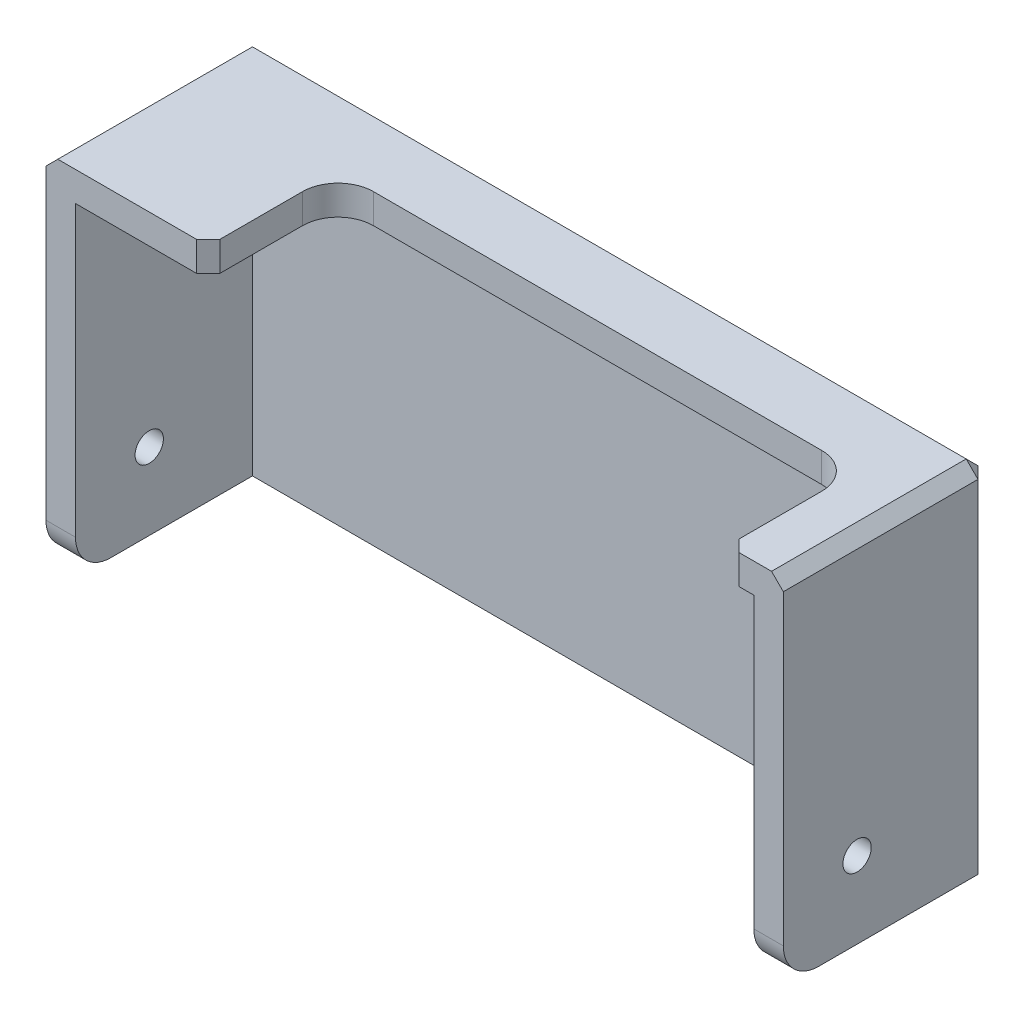
SolidWorks part; units mm, degrees
ref_plane "Front Plane" through (0, 0, 0) normal (0, 0, 1) x (1, 0, 0)
ref_plane "Top Plane" through (0, 0, 0) normal (0, 1, 0) x (1, 0, 0)
ref_plane "Right Plane" through (0, 0, 0) normal (1, 0, 0) x (0, 0, -1)
sketch "Sketch1" plane through (0, 0, 0) normal (0, 0, 1) x (1, 0, 0)
  line L1 (-57.5, -27.5) -> (57.5, -27.5)
  line L2 (-57.5, -27.5) -> (-57.5, 27.5)
  line L3 (-57.5, 27.5) -> (57.5, 27.5)
  line L4 (57.5, -27.5) -> (57.5, 27.5)
  line L5 (-57.5, -27.5) -> (57.5, 27.5) construction
  line L6 (-57.5, 27.5) -> (57.5, -27.5) construction
  point P0 (0, 0)
  dimension "D1" = 55
  dimension "D2" = 115
extrude "Boss-Extrude1" add sketch "Sketch1" along normal blind 30
sketch "Sketch2" plane through (0, 27.5, 0) normal (0, 1, 0) x (1, 0, 0)
  line L0 (57.5, -30) -> (-57.5, -30) construction
  line L1 (-35, -30) -> (53, -30)
  line L2 (-35, -30) -> (-35, -8)
  line L3 (-35, -8) -> (53, -8)
  line L4 (53, -30) -> (53, -8)
  line L6 (57.5, -30) -> (57.5, 0) construction
  line L7 (-57.5, -30) -> (-57.5, 0) construction
  dimension "D1" = 22.5
  dimension "D2" = 4.5
  dimension "D3" = 22
extrude "Cut-Extrude1" cut sketch "Sketch2" against normal through all
sketch "Sketch3" plane through (0, 0, 30) normal (0, 0, 1) x (1, 0, 0)
  line L0 (53, -27.5) -> (57.5, -27.5) construction
  line L1 (57.25, -27.5) -> (-57.25, -27.5)
  line L2 (57.25, -27.5) -> (57.25, 17.5)
  line L3 (57.25, 17.5) -> (-57.25, 17.5)
  line L4 (-57.25, -27.5) -> (-57.25, 17.5)
  line L5 (0, 17.5) -> (0, -27.5) construction
  line L7 (57.5, 27.5) -> (53, 27.5) construction
  dimension "D1" = 114.5
  dimension "D2" = 10
extrude "Cut-Extrude2" [suppressed] cut sketch "Sketch3" against normal blind 30
shell "Shell1" thickness 5
sketch "Sketch6" plane through (-62.5, 0, 0) normal (-1, 0, 0) x (0, 0, 1)
  line L0 (0, 27.5) -> (0, -27.5) construction
  line L1 (30, 27.5) -> (0, 27.5) construction
  point P0 (17.5, -14.5)
  dimension "D1" = 17.5
  dimension "D2" = 42
hole_wizard "M4 Clearance Hole1" positions "Sketch6" profile "Sketch5" hole size "M4" standard "ISO" end condition through all
sketch "Sketch5" plane through (-62.5, -14.5, 17.5) normal (0, 1, 0) x (0, 0, 1)
  line L0 (0, 0) -> (0, 125)
  line L1 (0, 125) -> (2.4, 125)
  line L2 (2.4, 125) -> (2.4, 0)
  line L5 (2.4, 0) -> (0, 0)
  line L11 (0, -6.35) -> (0, 107.95) construction
  dimension "Thru Hole Dia." = 4.8
  dimension "Thru Hole Depth" = 125
chamfer "Chamfer1" distance 2 angle 45 8 edges at (0, 32.5, -5) (62.5, 32.5, 12.5) (62.5, 2.5, -5) (0, -27.5, -5) (-62.5, 2.5, -5) (-62.5, 32.5, 12.5) (53, 30, 30) (-35, 30, 30)
fillet "Fillet1" radius 6 2 edges at (-35, 30, 8) (53, 30, 8)
fillet "Fillet2" radius 6 2 edges at (60, -27.5, 30) (-60, -27.5, 30)
